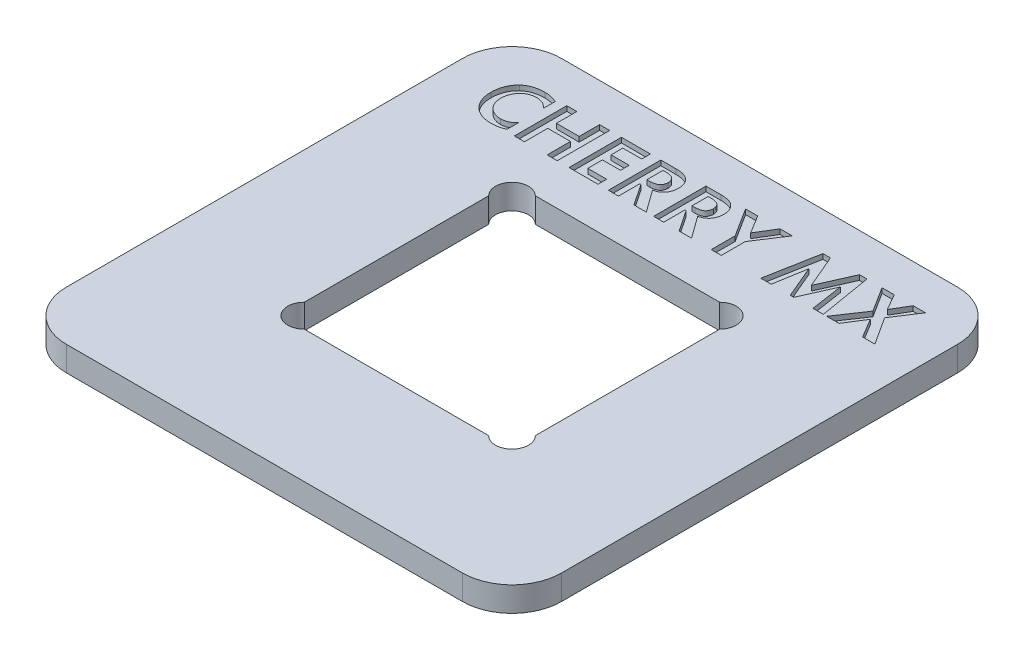
SolidWorks part; units mm, degrees
ref_plane "Front Plane" through (0, 0, 0) normal (0, 0, 1) x (1, 0, 0)
ref_plane "Top Plane" through (0, 0, 0) normal (0, 1, 0) x (1, 0, 0)
ref_plane "Right Plane" through (0, 0, 0) normal (1, 0, 0) x (0, 0, -1)
sketch "Sketch1" plane through (0, 0, 0) normal (0, 1, 0) x (1, 0, 0)
  line L1 (15, -15) -> (-15, -15)
  line L2 (15, -15) -> (15, 15)
  line L3 (15, 15) -> (-15, 15)
  line L4 (-15, -15) -> (-15, 15)
  line L5 (15, -15) -> (-15, 15) construction
  line L6 (15, 15) -> (-15, -15) construction
  point P0 (0, 0)
  dimension "D1" = 30
  dimension "D2" = 30
extrude "Boss-Extrude1" add sketch "Sketch1" against normal blind 1.5
sketch "Sketch2" plane through (0, 0, 0) normal (0, 1, 0) x (1, 0, 0)
  line L1 (7, -7) -> (-7, -7)
  line L2 (7, -7) -> (7, 7)
  line L3 (7, 7) -> (-7, 7)
  line L4 (-7, -7) -> (-7, 7)
  line L5 (7, -7) -> (-7, 7) construction
  line L6 (7, 7) -> (-7, -7) construction
  point P0 (0, 0)
  dimension "D1" = 14
  dimension "D2" = 14
extrude "Cut-Extrude1" cut sketch "Sketch2" against normal through all
sketch "Sketch4" plane through (0, 0, 0) normal (0, 1, 0) x (1, 0, 0)
  line L0 (-15, 9.501) -> (15, 9.501) construction
  line L1 (-15, 15) -> (-15, -15) construction
  line L2 (15, -15) -> (15, 15) construction
  text T0 "CHERRY MX" font "Futura PT Demi" height 3.175
extrude "Cut-Extrude2" cut sketch "Sketch4" against normal blind 0.3
fillet "Fillet1" radius 3 4 edges at (-15, -0.75, 15) (15, -0.75, 15) (-15, -0.75, -15) (15, -0.75, -15)
sketch "Sketch5" plane through (0, 0, 0) normal (0, 1, 0) x (1, 0, 0)
  line L0 (7, 7) -> (-7, 7) construction
  line L1 (-7, -7) -> (-7, 7) construction
  line L2 (7, -7) -> (-7, 7) construction
  line L3 (-7, 5.5858) -> (-5.5858, 7)
  line L4 (5.5858, 7) -> (7, 5.5858)
  line L5 (7, -5.5858) -> (5.5858, -7)
  line L6 (-5.5858, -7) -> (-7, -5.5858)
  arc A4 (-5.5858, 7) -> (-7, 5.5858) centre (-6.2929, 6.2929) ccw
  arc A5 (7, 5.5858) -> (5.5858, 7) centre (6.2929, 6.2929) ccw
  arc A6 (5.5858, -7) -> (7, -5.5858) centre (6.2929, -6.2929) ccw
  arc A7 (-7, -5.5858) -> (-5.5858, -7) centre (-6.2929, -6.2929) ccw
  point P26 (0, 0)
  dimension "D1" = 1
  dimension "D2" = 4
extrude "Cut-Extrude3" cut sketch "Sketch5" against normal through all
